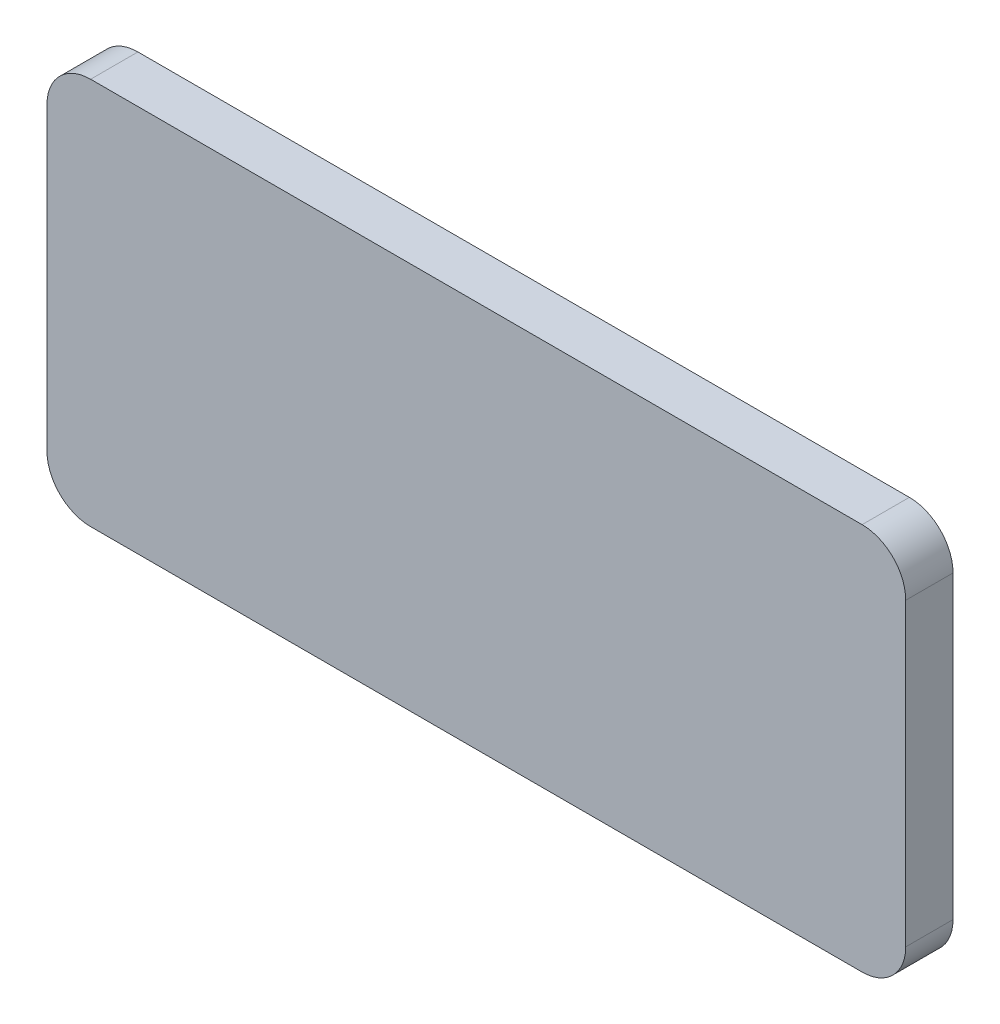
SolidWorks part; units mm, degrees
ref_plane "Plan de face" through (0, 0, 0) normal (0, 0, 1) x (1, 0, 0)
ref_plane "Plan de dessus" through (0, 0, 0) normal (0, 1, 0) x (1, 0, 0)
ref_plane "Plan de droite" through (0, 0, 0) normal (1, 0, 0) x (0, 0, -1)
sketch "Esquisse1" plane through (0, 0, 0) normal (0, 0, 1) x (1, 0, 0)
  line L1 (-24.48, -12.2955) -> (24.48, -12.2955)
  line L2 (-27.25, -9.5255) -> (-27.25, 9.5255)
  line L3 (-24.48, 12.2955) -> (24.48, 12.2955)
  line L4 (27.25, -9.5255) -> (27.25, 9.5255)
  line L5 (-27.25, -12.2955) -> (27.25, 12.2955) construction
  line L6 (-27.25, 12.2955) -> (27.25, -12.2955) construction
  arc A0 (-24.48, -12.2955) -> (-27.25, -9.5255) centre (-24.48, -9.5255) cw
  arc A1 (-27.25, 9.5255) -> (-24.48, 12.2955) centre (-24.48, 9.5255) cw
  arc A2 (24.48, 12.2955) -> (27.25, 9.5255) centre (24.48, 9.5255) cw
  arc A3 (24.48, -12.2955) -> (27.25, -9.5255) centre (24.48, -9.5255) ccw
  point P0 (0, 0)
  dimension "D2" = 2.77
  dimension "D1" = 54.5
  dimension "24" = 24.5909
extrude "Boss.-Extru.1" add sketch "Esquisse1" along normal blind 3
sketch "Esquisse2" plane through (0, 0, 3) normal (0, 0, 1) x (1, 0, 0)
  line L0 (-14.65, 3.9887) -> (-14.65, 2.4887) construction
  line L1 (24.48, 12.2955) -> (-24.48, 12.2955) construction
  line L6 (-14.65, 2.4887) -> (14.03, 2.4887) construction
  line L10 (-15.5031, 12.2955) -> (-6.9031, 12.2955)
  point P2 (-11.2031, 7.4042)
  point P13 (-0.4772, 6.2907)
  point P14 (0.2479, 7.4042)
  dimension "D1" = 1.5
extrude "Enlèv. mat.-Extru.1" cut sketch "Esquisse2" against normal blind 10
